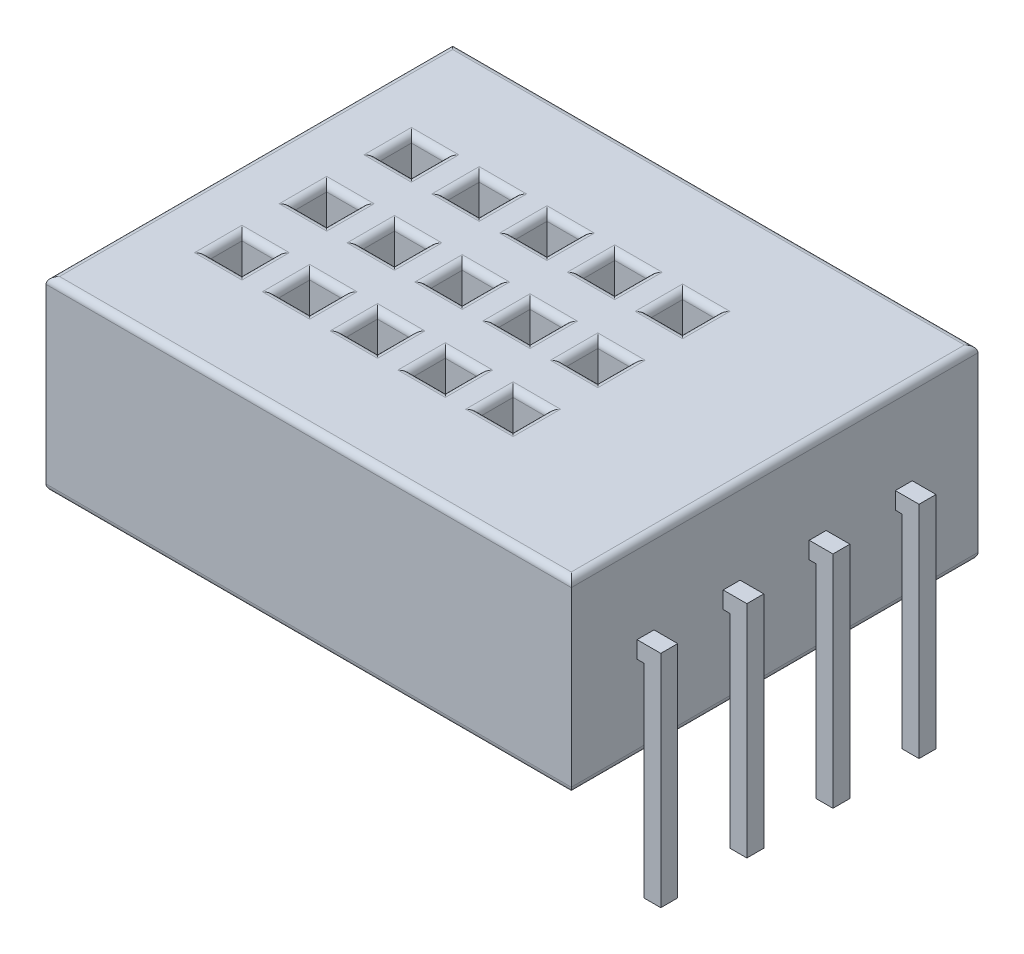
SolidWorks part; units mm, degrees
ref_plane "Front Plane" through (0, 0, 0) normal (0, 0, 1) x (1, 0, 0)
ref_plane "Top Plane" through (0, 0, 0) normal (0, 1, 0) x (1, 0, 0)
ref_plane "Right Plane" through (0, 0, 0) normal (1, 0, 0) x (0, 0, -1)
sketch "Sketch1" plane through (0, 0, 0) normal (0, 1, 0) x (1, 0, 0)
  line L1 (0, 0) -> (15.5, 0)
  line L2 (0, 0) -> (0, -12)
  line L3 (0, -12) -> (15.5, -12)
  line L4 (15.5, 0) -> (15.5, -12)
  dimension "D1" = 12
  dimension "D2" = 15.5
extrude "Boss-Extrude1" add sketch "Sketch1" along normal blind 5.5
sketch "Sketch2" plane through (15.5, 0, 0) normal (1, 0, 0) x (0, 0, -1)
  line L0 (-12, 2.75) -> (-9.81, 2.75) construction
  line L1 (-12, 5.5) -> (-12, 0) construction
  line L2 (-9.81, 2.75) -> (-7.27, 2.75) construction
  line L3 (-7.27, 2.75) -> (-4.73, 2.75) construction
  line L4 (-4.73, 2.75) -> (-2.19, 2.75) construction
  line L5 (-2.19, 2.75) -> (0, 2.75) construction
  line L6 (0, 5.5) -> (0, 0) construction
  line L8 (-9.56, 3) -> (-10.06, 3)
  line L9 (-9.56, 3) -> (-9.56, 2.5)
  line L10 (-9.56, 2.5) -> (-10.06, 2.5)
  line L11 (-10.06, 3) -> (-10.06, 2.5)
  line L12 (-7.02, 3) -> (-7.52, 3)
  line L13 (-7.02, 3) -> (-7.02, 2.5)
  line L14 (-7.02, 2.5) -> (-7.52, 2.5)
  line L15 (-7.52, 3) -> (-7.52, 2.5)
  line L16 (-4.48, 3) -> (-4.98, 3)
  line L17 (-4.48, 3) -> (-4.48, 2.5)
  line L18 (-4.48, 2.5) -> (-4.98, 2.5)
  line L19 (-4.98, 3) -> (-4.98, 2.5)
  line L20 (-2.44, 3) -> (-1.94, 3)
  line L21 (-2.44, 3) -> (-2.44, 2.5)
  line L22 (-2.44, 2.5) -> (-1.94, 2.5)
  line L23 (-1.94, 3) -> (-1.94, 2.5)
  circle A0 centre (-9.81, 2.75) radius 0.25 construction
  circle A1 centre (-7.27, 2.75) radius 0.25 construction
  circle A2 centre (-4.73, 2.75) radius 0.25 construction
  circle A3 centre (-2.19, 2.75) radius 0.25 construction
  dimension "D2" = 0.5
  dimension "D1" = 2.54
extrude "Boss-Extrude2" add sketch "Sketch2" along normal blind 0.7
sketch "Sketch3" plane through (0, 2.5, 0) normal (0, -1, 0) x (1, 0, 0)
  line L0 (16.2, 9.56) -> (15.5, 9.56) construction
  line L1 (16.2, 10.06) -> (15.7, 10.06)
  line L2 (16.2, 10.06) -> (16.2, 9.56)
  line L3 (16.2, 9.56) -> (15.7, 9.56)
  line L4 (15.7, 10.06) -> (15.7, 9.56)
  line L5 (16.2, 7.02) -> (15.5, 7.02) construction
  line L6 (16.2, 7.52) -> (15.7, 7.52)
  line L7 (16.2, 7.52) -> (16.2, 7.02)
  line L8 (16.2, 7.02) -> (15.7, 7.02)
  line L9 (15.7, 7.52) -> (15.7, 7.02)
  line L10 (16.2, 4.48) -> (15.5, 4.48) construction
  line L11 (16.2, 4.98) -> (15.7, 4.98)
  line L12 (16.2, 4.98) -> (16.2, 4.48)
  line L13 (16.2, 4.48) -> (15.7, 4.48)
  line L14 (15.7, 4.98) -> (15.7, 4.48)
  line L15 (16.2, 1.94) -> (15.5, 1.94) construction
  line L16 (16.2, 2.44) -> (15.7, 2.44)
  line L17 (16.2, 2.44) -> (16.2, 1.94)
  line L18 (16.2, 1.94) -> (15.7, 1.94)
  line L19 (15.7, 2.44) -> (15.7, 1.94)
extrude "Boss-Extrude3" add sketch "Sketch3" along normal blind 6
sketch "Sketch4" plane through (0, 5.5, 0) normal (0, 1, 0) x (1, 0, 0)
  line L0 (0, 0) -> (1.7817, 0) construction
  line L1 (15.5, 0) -> (0, 0) construction
  line L2 (1.7817, 0) -> (1.7817, -3) construction
  line L3 (1.7817, -3) -> (1.7817, -4) construction
  line L4 (1.7817, -4) -> (1.7817, -5.5) construction
  line L5 (1.7817, -5.5) -> (1.7817, -6.5) construction
  line L6 (1.7817, -6.5) -> (1.7817, -8) construction
  line L7 (1.7817, -8) -> (1.7817, -9) construction
  line L8 (1.7817, -9) -> (1.7817, -12) construction
  line L9 (0, -12) -> (15.5, -12) construction
  line L11 (1.7817, -3) -> (2.7817, -3)
  line L12 (1.7817, -3) -> (1.7817, -4)
  line L13 (1.7817, -4) -> (2.7817, -4)
  line L14 (2.7817, -3) -> (2.7817, -4)
  line L15 (1.7817, -5.5) -> (2.7817, -5.5)
  line L16 (1.7817, -5.5) -> (1.7817, -6.5)
  line L17 (1.7817, -6.5) -> (2.7817, -6.5)
  line L18 (2.7817, -5.5) -> (2.7817, -6.5)
  line L19 (1.7817, -8) -> (2.7817, -8)
  line L20 (1.7817, -8) -> (1.7817, -9)
  line L21 (1.7817, -9) -> (2.7817, -9)
  line L22 (2.7817, -8) -> (2.7817, -9)
  dimension "D1" = 1
  dimension "D2" = 3
extrude "Cut-Extrude1" cut sketch "Sketch4" against normal blind 3
pattern_linear "LPattern1" count 5 spacing 2 along (1, 0, 0) of "Cut-Extrude1"
fillet "Fillet1" radius 0.2 64 edges at (10.2817, 5.5, 6.5) (10.7817, 5.5, 6) (10.2817, 5.5, 5.5) (9.7817, 5.5, 6) (8.2817, 5.5, 6.5) (8.7817, 5.5, 6) (8.2817, 5.5, 5.5) (7.7817, 5.5, 6) (6.2817, 5.5, 6.5) (6.7817, 5.5, 6) (6.2817, 5.5, 5.5) (5.7817, 5.5, 6) (10.2817, 5.5, 9) (10.7817, 5.5, 8.5) (10.2817, 5.5, 8) (9.7817, 5.5, 8.5) (8.2817, 5.5, 9) (8.7817, 5.5, 8.5) (8.2817, 5.5, 8) (7.7817, 5.5, 8.5) (6.2817, 5.5, 9) (6.7817, 5.5, 8.5) (6.2817, 5.5, 8) (5.7817, 5.5, 8.5) (10.2817, 5.5, 3) (9.7817, 5.5, 3.5) (10.2817, 5.5, 4) (10.7817, 5.5, 3.5) (8.2817, 5.5, 3) (7.7817, 5.5, 3.5) (8.2817, 5.5, 4) (8.7817, 5.5, 3.5) (6.2817, 5.5, 3) (5.7817, 5.5, 3.5) (6.2817, 5.5, 4) (6.7817, 5.5, 3.5) (7.75, 5.5, 0) (15.5, 5.5, 6) (7.75, 5.5, 12) (0, 5.5, 6) (2.2817, 5.5, 9) (2.7817, 5.5, 8.5) (2.2817, 5.5, 8) (1.7817, 5.5, 8.5) (2.2817, 5.5, 6.5) (2.7817, 5.5, 6) (2.2817, 5.5, 5.5) (1.7817, 5.5, 6) (2.2817, 5.5, 3) (1.7817, 5.5, 3.5) (2.2817, 5.5, 4) (2.7817, 5.5, 3.5) (4.2817, 5.5, 3) (3.7817, 5.5, 3.5) (4.2817, 5.5, 4) (4.7817, 5.5, 3.5) (4.2817, 5.5, 9) (4.7817, 5.5, 8.5) (4.2817, 5.5, 8) (3.7817, 5.5, 8.5) (4.2817, 5.5, 6.5) (4.7817, 5.5, 6) (4.2817, 5.5, 5.5) (3.7817, 5.5, 6)
fillet "Fillet2" radius 0.2 4 edges at (7.75, 0, 12) (15.5, 0, 6) (7.75, 0, 0) (0, 0, 6)
